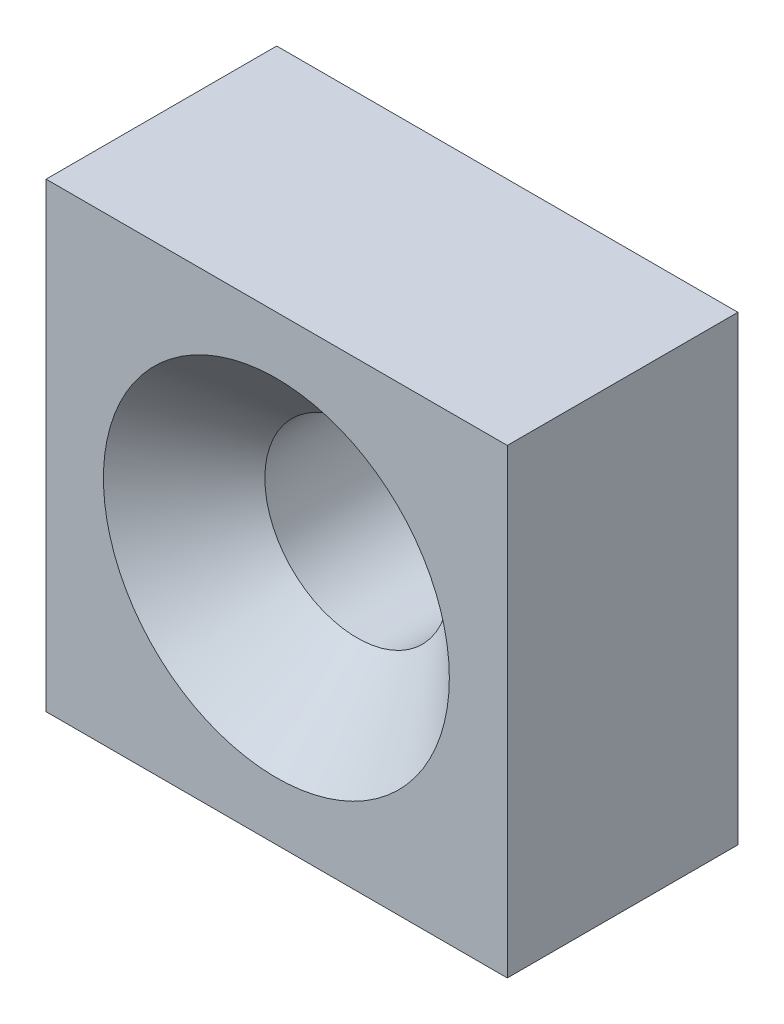
SolidWorks part; units mm, degrees
ref_plane "前视基准面" through (0, 0, 0) normal (0, 0, 1) x (1, 0, 0)
ref_plane "上视基准面" through (0, 0, 0) normal (0, 1, 0) x (1, 0, 0)
ref_plane "右视基准面" through (0, 0, 0) normal (1, 0, 0) x (0, 0, -1)
other "Configuration Table"
sketch "草图1" plane through (0, 0, 0) normal (0, 0, 1) x (1, 0, 0)
  line L1 (0, 0) -> (20, 0)
  line L2 (0, 0) -> (0, 20)
  line L3 (0, 20) -> (20, 20)
  line L4 (20, 0) -> (20, 20)
extrude "BaseBox" add sketch "草图1" along normal blind 10
hole_wizard "Hole_cs_iso_flathead_m8" positions "草图3" profile "草图2" countersink size "M8" standard "ISO" end condition through all
sketch "草图3" plane through (0, 0, 10) normal (0, 0, 1) x (1, 0, 0)
  point P0 (9.9865, 10.0143)
sketch "草图2" plane through (9.9865, 10.0143, 10) normal (1, 0, 0) x (0, -1, 0)
  line L0 (0, 0) -> (0, 10)
  line L1 (0, 10) -> (4, 10)
  line L2 (4, 10) -> (4, 3.5)
  line L3 (4, 3.5) -> (7.5, 0)
  line L5 (7.5, 0) -> (0, 0)
  line L6 (-4, 3.5) -> (-7.5, 0) construction
  line L11 (0, -6.35) -> (0, 107.95) construction
  dimension "通孔孔直径" = 8
  dimension "通孔孔深度" = 10
  dimension "近端锥形沉头孔直径" = 15
  dimension "近端锥形沉头孔角度" = 90
